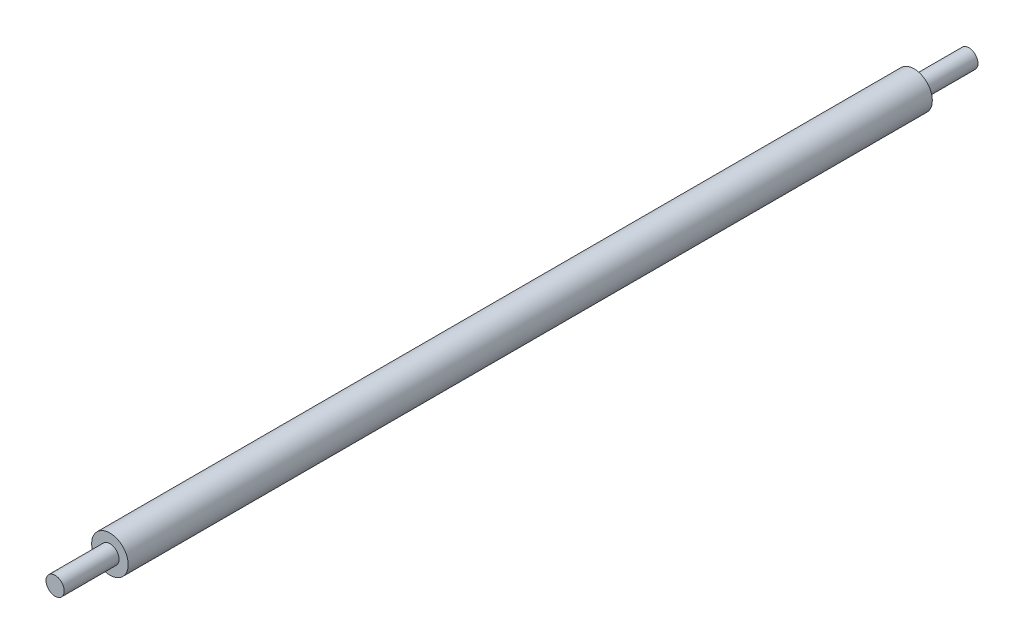
SolidWorks part; units mm, degrees
ref_plane "Alzado" through (0, 0, 0) normal (0, 0, 1) x (1, 0, 0)
ref_plane "Planta" through (0, 0, 0) normal (0, 1, 0) x (1, 0, 0)
ref_plane "Vista lateral" through (0, 0, 0) normal (1, 0, 0) x (0, 0, -1)
sketch "Croquis1" plane through (0, 0, 0) normal (0, 0, 1) x (1, 0, 0)
  circle A0 centre (0, 0) radius 0.05
  dimension "D1" = 0.1
extrude "Saliente-Extruir1" add sketch "Croquis1" along normal blind 2.5
ref_plane "Plano1" through (0, 0, 0.15) normal (0, 0, 1) x (1, 0, 0)
sketch "Croquis3" plane through (0, 0, 0.15) normal (0, 0, 1) x (1, 0, 0)
  circle A0 centre (0, 0) radius 0.05
  dimension "D1" = 0.1
extrude "Cortar-Extruir1" cut sketch "Croquis3" against normal through all
sketch "Croquis4" plane through (0, 0, 0.15) normal (0, 0, 1) x (1, 0, 0)
  circle A0 centre (0, 0) radius 0.025
  dimension "D1" = 0.05
extrude "Saliente-Extruir2" add sketch "Croquis4" against normal blind 0.15
ref_plane "Plano2" through (0, 0, 2.35) normal (0, 0, 1) x (1, 0, 0)
sketch "Croquis5" plane through (0, 0, 2.35) normal (0, 0, 1) x (1, 0, 0)
  circle A0 centre (0, 0) radius 0.05
  dimension "D1" = 0.1
extrude "Cortar-Extruir2" cut sketch "Croquis5" along normal blind 0.15
sketch "Croquis6" plane through (0, 0, 2.35) normal (0, 0, 1) x (1, 0, 0)
  circle A0 centre (0, 0) radius 0.025
  dimension "D1" = 0.0499
extrude "Saliente-Extruir3" add sketch "Croquis6" along normal blind 0.15
